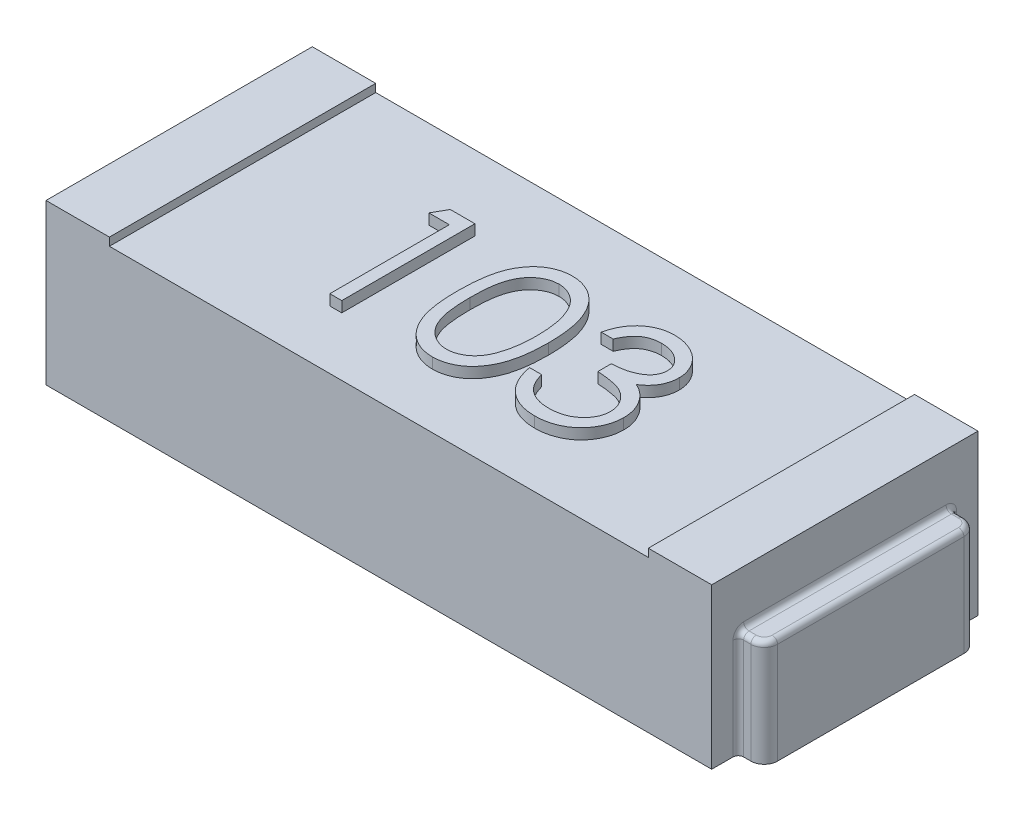
SolidWorks part; units mm, degrees
ref_plane "Plan de face" through (0, 0, 0) normal (0, 0, 1) x (1, 0, 0)
ref_plane "Plan de dessus" through (0, 0, 0) normal (0, 1, 0) x (1, 0, 0)
ref_plane "Plan de droite" through (0, 0, 0) normal (1, 0, 0) x (0, 0, -1)
sketch "Esquisse1" plane through (0, 0, 0) normal (0, 1, 0) x (1, 0, 0)
  line L1 (1.25, -0.5) -> (-1.25, -0.5)
  line L2 (1.25, -0.5) -> (1.25, 0.5)
  line L3 (1.25, 0.5) -> (-1.25, 0.5)
  line L4 (-1.25, -0.5) -> (-1.25, 0.5)
  line L5 (1.25, -0.5) -> (-1.25, 0.5) construction
  line L6 (1.25, 0.5) -> (-1.25, -0.5) construction
  point P0 (0, 0)
  dimension "D1" = 2.5
  dimension "D2" = 1
extrude "Boss.-Extru.1" add sketch "Esquisse1" along normal blind 0.6
sketch "Esquisse2" plane through (0, 0.6, 0) normal (0, 1, 0) x (1, 0, 0)
  line L0 (1.25, 0.5) -> (-1.25, 0.5) construction
  line L1 (1.0118, -0.5) -> (-1.0118, -0.5)
  line L2 (1.0118, -0.5) -> (1.0118, 0.5)
  line L3 (1.0118, 0.5) -> (-1.0118, 0.5)
  line L4 (-1.0118, -0.5) -> (-1.0118, 0.5)
  line L5 (1.0118, -0.5) -> (-1.0118, 0.5) construction
  line L6 (1.0118, 0.5) -> (-1.0118, -0.5) construction
  point P0 (0, 0)
extrude "Enlèv. mat.-Extru.1" cut sketch "Esquisse2" against normal blind 0.03
sketch "Esquisse3" plane through (0, 0, 0) normal (0, 1, 0) x (1, 0, 0)
  line L0 (1.25, -0.5) -> (1.25, 0.5) construction
  line L1 (1.25, 0.4) -> (1.2971, 0.4)
  line L2 (1.25, 0.4) -> (1.25, -0.4)
  line L3 (1.25, -0.4) -> (1.2971, -0.4)
  line L4 (1.3471, 0.35) -> (1.3471, -0.35)
  line L5 (1.25, 0.5) -> (1.0118, 0.5) construction
  line L6 (1.0118, -0.5) -> (1.25, -0.5) construction
  arc A0 (1.2971, -0.4) -> (1.3471, -0.35) centre (1.2971, -0.35) ccw
  arc A1 (1.2971, 0.4) -> (1.3471, 0.35) centre (1.2971, 0.35) cw
  dimension "D1" = 0.05
  dimension "D2" = 0.1
  dimension "D3" = 0.1
extrude "Boss.-Extru.2" add sketch "Esquisse3" along normal blind 0.4
fillet "Congé1" radius 0.02 8 edges at (1.25, 0.2, -0.4) (1.25, 0.2, 0.4) (1.2736, 0.4, -0.4) (1.3325, 0.4, -0.3854) (1.3471, 0.4, 0) (1.3325, 0.4, 0.3854) (1.2736, 0.4, 0.4) (1.25, 0.4, 0)
mirror "Symétrie2" about plane through (0, 0, 0) normal (1, 0, 0) of "Congé1", "Boss.-Extru.2"
sketch "Esquisse4" plane through (0, 0.57, 0) normal (0, 1, 0) x (1, 0, 0)
  line L0 (0.7576, -0.2803) -> (-0.7576, -0.2803) construction
  text T0 "103" font "Century Gothic" height 0.5
  point P3 (0, -0.2803)
extrude "Boss.-Extru.3" add sketch "Esquisse4" along normal blind 0.04
